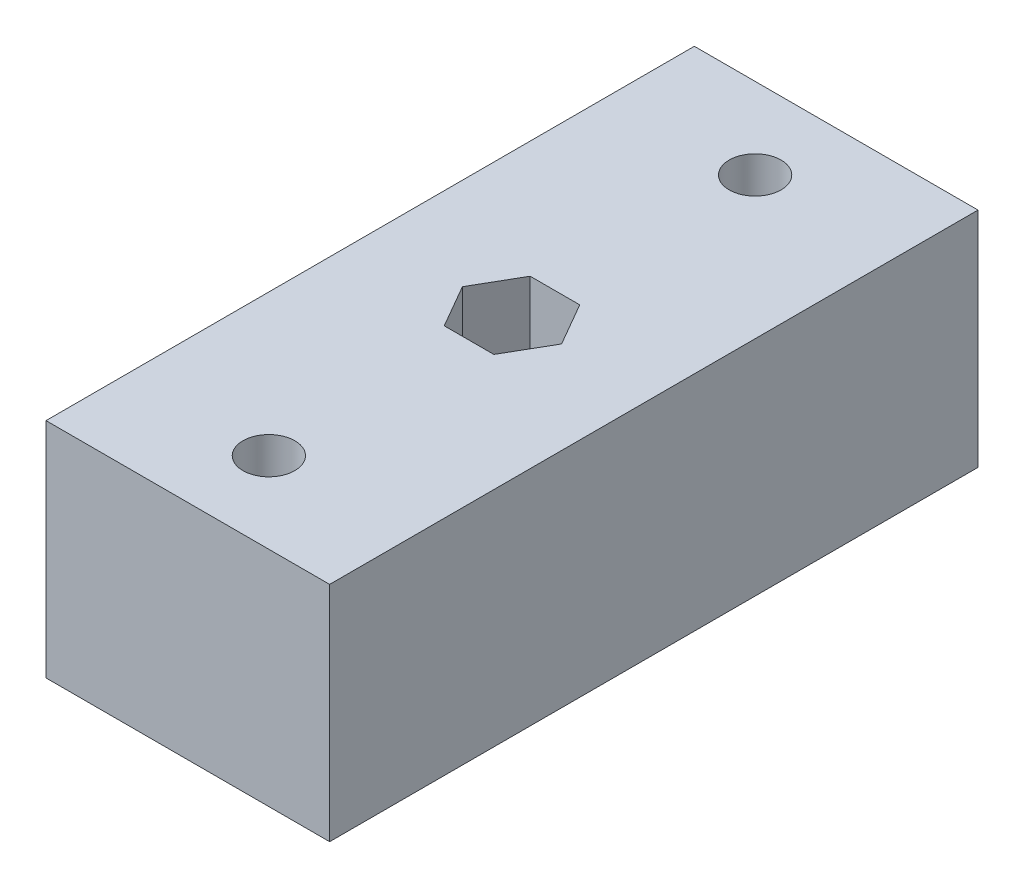
SolidWorks part; units mm, degrees
ref_plane "Front Plane" through (0, 0, 0) normal (0, 0, 1) x (1, 0, 0)
ref_plane "Top Plane" through (0, 0, 0) normal (0, 1, 0) x (1, 0, 0)
ref_plane "Right Plane" through (0, 0, 0) normal (1, 0, 0) x (0, 0, -1)
sketch "Sketch1" plane through (0, 0, 0) normal (0, 0, 1) x (1, 0, 0)
  line L1 (0, 0) -> (22.225, 0)
  line L2 (0, 0) -> (0, 17.4625)
  line L3 (0, 17.4625) -> (22.225, 17.4625)
  line L4 (22.225, 0) -> (22.225, 17.4625)
  dimension "D1" = 17.4625
  dimension "D2" = 22.225
extrude "Boss-Extrude1" add sketch "Sketch1" along normal blind 50.8
sketch "Sketch2" plane through (0, 0, 0) normal (0, -1, 0) x (1, 0, 0)
  line L0 (0, 50.8) -> (0, 0) construction
  line L1 (14.9986, 25.4) -> (13.0556, 28.7655)
  line L2 (13.0556, 28.7655) -> (9.1694, 28.7655)
  line L3 (9.1694, 28.7655) -> (7.2264, 25.4)
  line L4 (7.2264, 25.4) -> (9.1694, 22.0345)
  line L5 (9.1694, 22.0345) -> (13.0556, 22.0345)
  line L6 (13.0556, 22.0345) -> (14.9986, 25.4)
  line L7 (0, 50.8) -> (22.225, 50.8) construction
  circle A0 centre (11.1125, 25.4) radius 3.3655 construction
  circle A5 centre (11.1125, 44.45) radius 2.032
  circle A6 centre (11.1125, 6.35) radius 2.032
  point P1 (0, 25.4)
  point P13 (11.1125, 50.8)
  point P18 (11.0998, -2.297)
  point P19 (11.1125, 35.6759)
  point P20 (11.1125, -3.0198)
  dimension "D2" = 4.064
  dimension "D1" = 6.731
  dimension "D3" = 38.1
  dimension "D4" = 19.05
extrude "Cut-Extrude1" cut sketch "Sketch2" against normal up to next
